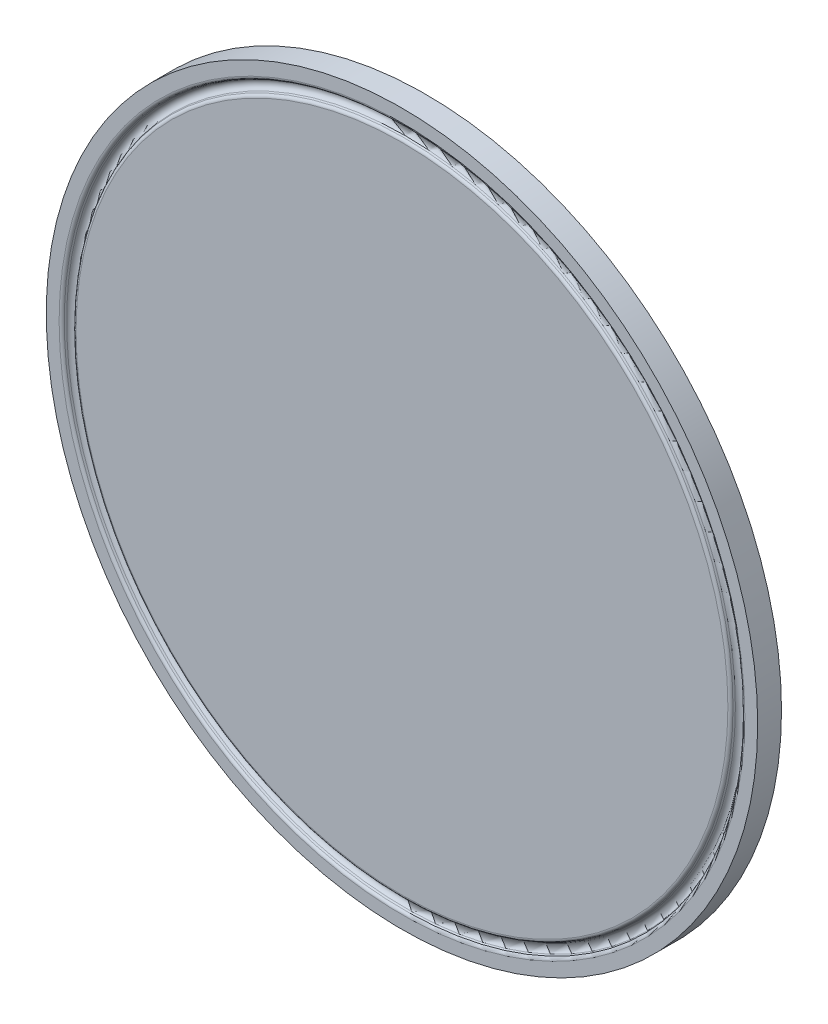
SolidWorks part; units mm, degrees
ref_plane "Front Plane" through (0, 0, 0) normal (0, 0, 1) x (1, 0, 0)
ref_plane "Top Plane" through (0, 0, 0) normal (0, 1, 0) x (1, 0, 0)
ref_plane "Right Plane" through (0, 0, 0) normal (1, 0, 0) x (0, 0, -1)
sketch "Sketch1" plane through (0, 0, 0) normal (1, 0, 0) x (0, 0, -1)
  line L0 (0, 0) -> (11.0998, 0) construction
  line L1 (0, 0) -> (0, 76.4446)
  line L2 (0, 83.439) -> (5.588, 83.439)
  line L3 (5.588, 83.439) -> (11.0998, 68.2955)
  line L4 (11.0998, 68.2955) -> (11.0998, 0)
  line L5 (0, 80.4258) -> (0, 83.439)
  line L6 (0.4797, 79.701) -> (0.8729, 79.5341)
  line L7 (0.4797, 77.1694) -> (0.8729, 77.3363)
  line L8 (0, 79.9046) -> (0, 76.9658) construction
  line L9 (0, 78.4352) -> (0.4064, 78.4352) construction
  line L10 (0, 0) -> (11.0998, 0)
  arc A0 (0.8729, 77.3363) -> (0.8729, 79.5341) centre (0.4064, 78.4352) ccw
  arc A2 (0, 76.4446) -> (0.4797, 77.1694) centre (0.7874, 76.4446) cw
  arc A3 (0, 80.4258) -> (0.4797, 79.701) centre (0.7874, 80.4258) ccw
  dimension "K" = 1.1938
  dimension "L" = 0.7874
  dimension "I" = 20
  dimension "C" = 136.5909
  dimension "F" = 5.588
  dimension "H" = 0.4064
  dimension "B" = 156.8704
  dimension "A" = 166.878
  dimension "M" = 46
  dimension "N" = 23
  dimension "Length" = 11.0998
revolve "Revolve1" add sketch "Sketch1" angle 360 about L0
